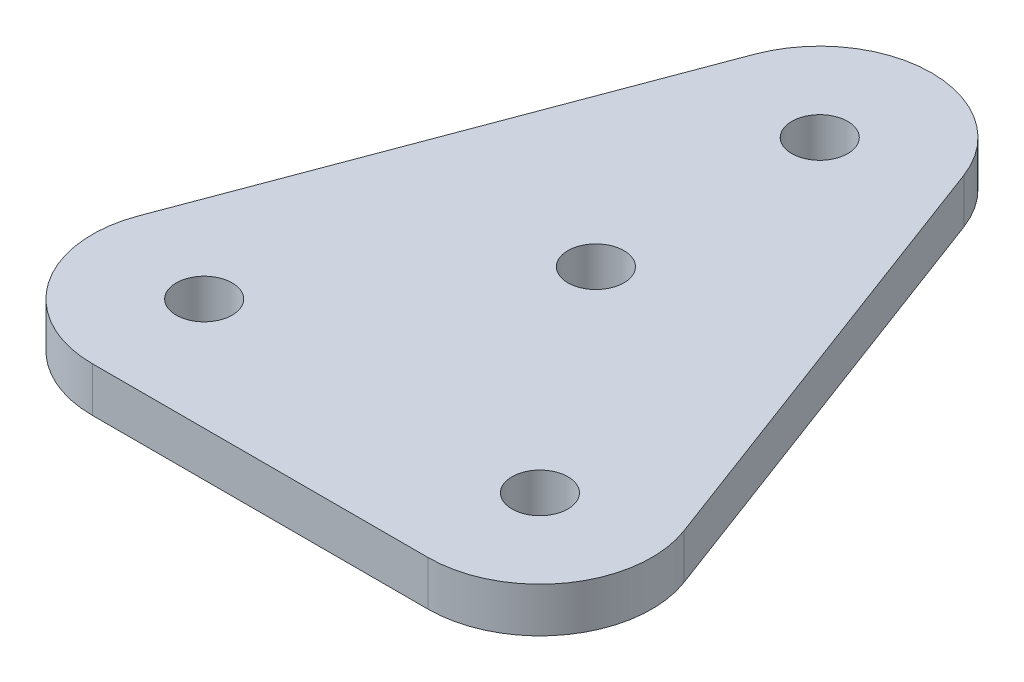
SolidWorks part; units mm, degrees
material "Thornel Mat VMA"
ref_plane "Front Plane" through (0, 0, 0) normal (0, 0, 1) x (1, 0, 0)
ref_plane "Top Plane" through (0, 0, 0) normal (0, 1, 0) x (1, 0, 0)
ref_plane "Right Plane" through (0, 0, 0) normal (1, 0, 0) x (0, 0, -1)
sketch "Sketch1" plane through (0, 0, 0) normal (0, 1, 0) x (1, 0, 0)
  line L0 (0, 48.5704) -> (0, -31.4177) construction
  line L1 (-41.6317, 0) -> (40.9422, 0) construction
  line L2 (-9.3633, 43.5112) -> (-24.3633, 3.5112)
  line L3 (-15, -10) -> (15, -10)
  line L4 (9.3633, 43.5112) -> (24.3633, 3.5112)
  circle A0 centre (15, 0) radius 2.5
  circle A1 centre (-15, 0) radius 2.5
  circle A2 centre (0, 20) radius 2.5
  circle A3 centre (0, 40) radius 2.5
  arc A4 (9.3633, 43.5112) -> (-9.3633, 43.5112) centre (0, 40) ccw
  arc A5 (-24.3633, 3.5112) -> (-15, -10) centre (-15, 0) ccw
  arc A6 (15, -10) -> (24.3633, 3.5112) centre (15, 0) ccw
  dimension "D1" = 5
  dimension "D3" = 5
  dimension "D5" = 5
  dimension "D7" = 20
  dimension "D8" = 20
  dimension "D9" = 20
  dimension "D2" = 15
  dimension "D4" = 20
  dimension "D6" = 40
extrude "Boss-Extrude1" add sketch "Sketch1" along normal blind 4
